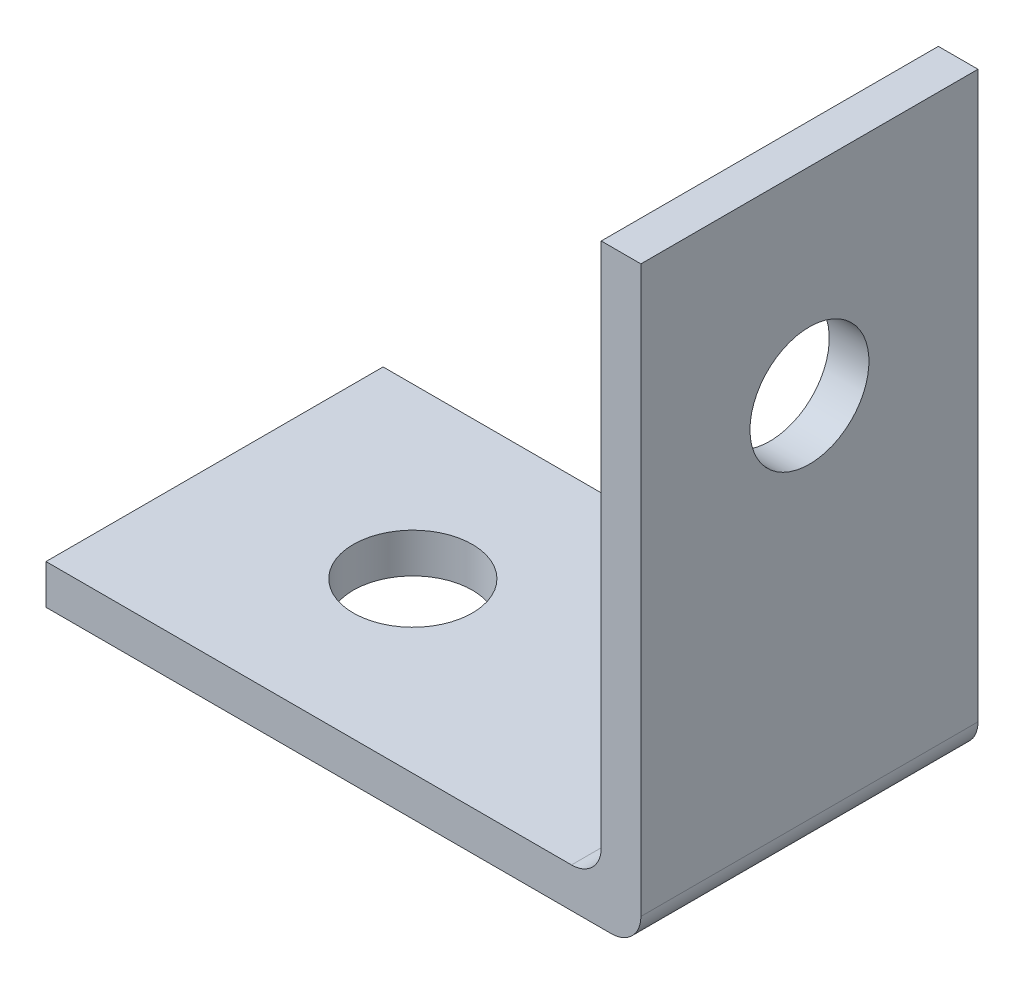
SolidWorks part; units mm, degrees
ref_plane "Front Plane" through (0, 0, 0) normal (0, 0, 1) x (1, 0, 0)
ref_plane "Top Plane" through (0, 0, 0) normal (0, 1, 0) x (1, 0, 0)
ref_plane "Right Plane" through (0, 0, 0) normal (1, 0, 0) x (0, 0, -1)
sketch "Sketch2" plane through (0, 0, 0) normal (0, 0, 1) x (1, 0, 0)
  line L0 (0, 0) -> (28.5, 0)
  line L1 (30, 1.5) -> (30, 30)
  line L2 (30, 30) -> (28, 30)
  line L3 (28, 30) -> (28, 3.5)
  line L4 (26.5, 2) -> (0, 2)
  line L5 (0, 2) -> (0, 0)
  arc A0 (28, 3.5) -> (26.5, 2) centre (26.5, 3.5) cw
  arc A1 (28.5, 0) -> (30, 1.5) centre (28.5, 1.5) ccw
  point P11 (30, 0)
  dimension "D5" = 1.5
  dimension "D1" = 30
  dimension "D2" = 30
  dimension "D3" = 2
  dimension "D4" = 2
extrude "Boss-Extrude1" add sketch "Sketch2" along normal blind 17
sketch "Sketch3" plane through (28, 0, 0) normal (-1, 0, 0) x (0, 0, 1)
  line L0 (0, 30) -> (0, 3.5) construction
  line L1 (17, 30) -> (0, 30) construction
  circle A0 centre (8.5, 20) radius 3
  dimension "D1" = 6
  dimension "D2" = 8.5
  dimension "D3" = 10
extrude "Cut-Extrude1" cut sketch "Sketch3" against normal through all
sketch "Sketch4" plane through (0, 2, 0) normal (0, 1, 0) x (1, 0, 0)
  line L0 (26.5, 0) -> (0, 0) construction
  line L1 (0, -17) -> (0, 0) construction
  circle A0 centre (10, -8.5) radius 3
  dimension "D1" = 6
  dimension "D2" = 8.5
  dimension "D3" = 10
extrude "Cut-Extrude2" cut sketch "Sketch4" against normal through all
